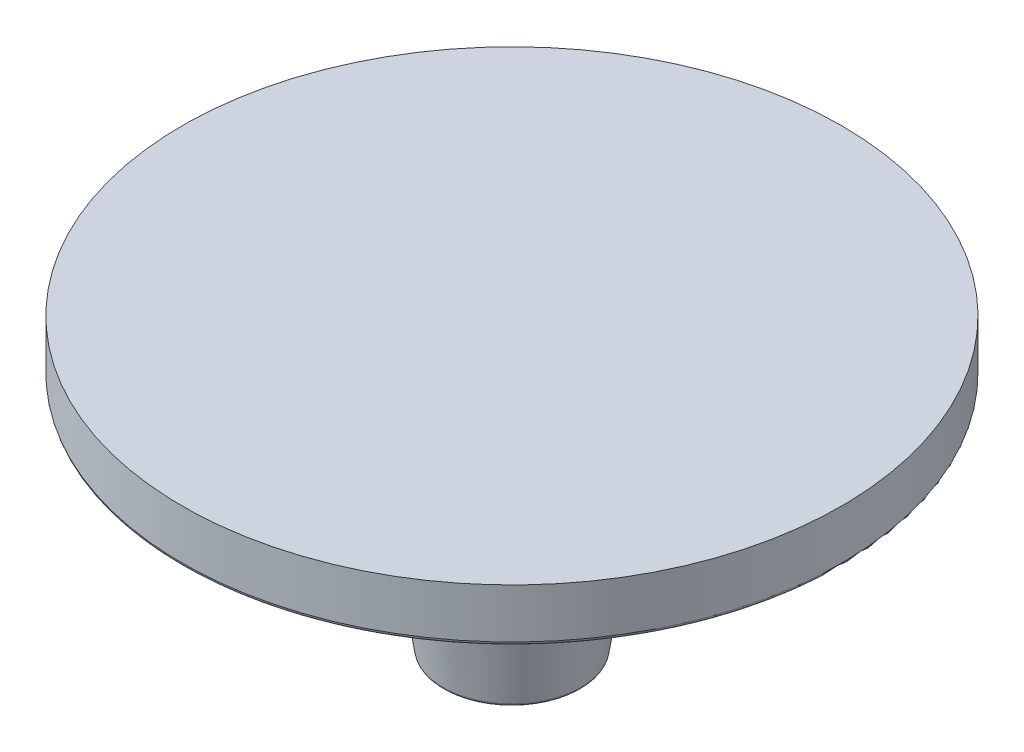
SolidWorks part; units mm, degrees
material "ABS"
ref_plane "Front Plane" through (0, 0, 0) normal (0, 0, 1) x (1, 0, 0)
ref_plane "Top Plane" through (0, 0, 0) normal (0, 1, 0) x (1, 0, 0)
ref_plane "Right Plane" through (0, 0, 0) normal (1, 0, 0) x (0, 0, -1)
sketch "Sketch2" plane through (0, 0, 0) normal (0, 0, 1) x (1, 0, 0)
  line L0 (3.2286, 12.0939) -> (2.4214, 20.6409)
  line L1 (2.1725, 20.8674) -> (0, 20.8674)
  line L2 (0, 20.8674) -> (0, 33.8674)
  line L3 (0, 33.8674) -> (25, 33.8674)
  line L6 (25, 33.8674) -> (25, 30.1174)
  line L7 (22.75, 30.8674) -> (8.2473, 30.8674)
  line L8 (8, 30.6543) -> (5.2286, 12.0805)
  line L9 (4.9813, 11.8674) -> (3.4775, 11.8674)
  line L10 (23, 30.6174) -> (23, 30.1174)
  line L11 (23.25, 29.8674) -> (24.75, 29.8674)
  arc A0 (5.2286, 12.0805) -> (4.9813, 11.8674) centre (4.9813, 12.1174) cw
  arc A1 (3.2286, 12.0939) -> (3.4775, 11.8674) centre (3.4775, 12.1174) ccw
  arc A2 (2.4214, 20.6409) -> (2.1725, 20.8674) centre (2.1725, 20.6174) ccw
  arc A3 (24.75, 29.8674) -> (25, 30.1174) centre (24.75, 30.1174) ccw
  arc A4 (23, 30.1174) -> (23.25, 29.8674) centre (23.25, 30.1174) ccw
  arc A5 (23, 30.6174) -> (22.75, 30.8674) centre (22.75, 30.6174) ccw
  arc A6 (8.2473, 30.8674) -> (8, 30.6543) centre (8.2473, 30.6174) ccw
  point P17 (3.25, 11.8674)
  point P20 (2.4, 20.8674)
  point P23 (25, 29.8674)
  point P26 (23, 29.8674)
  point P29 (23, 30.8674)
  dimension "D9" = 0.25
  dimension "D10" = 0.25
  dimension "D1" = 3.25
  dimension "D2" = 2.4
  dimension "D3" = 9
  dimension "D4" = 3
  dimension "D5" = 2
  dimension "D6" = 10
  dimension "D7" = 2
  dimension "D8" = 1
  dimension "D11" = 25
  dimension "D12" = 8
revolve "Revolve1" add sketch "Sketch2" angle 360 about L2
